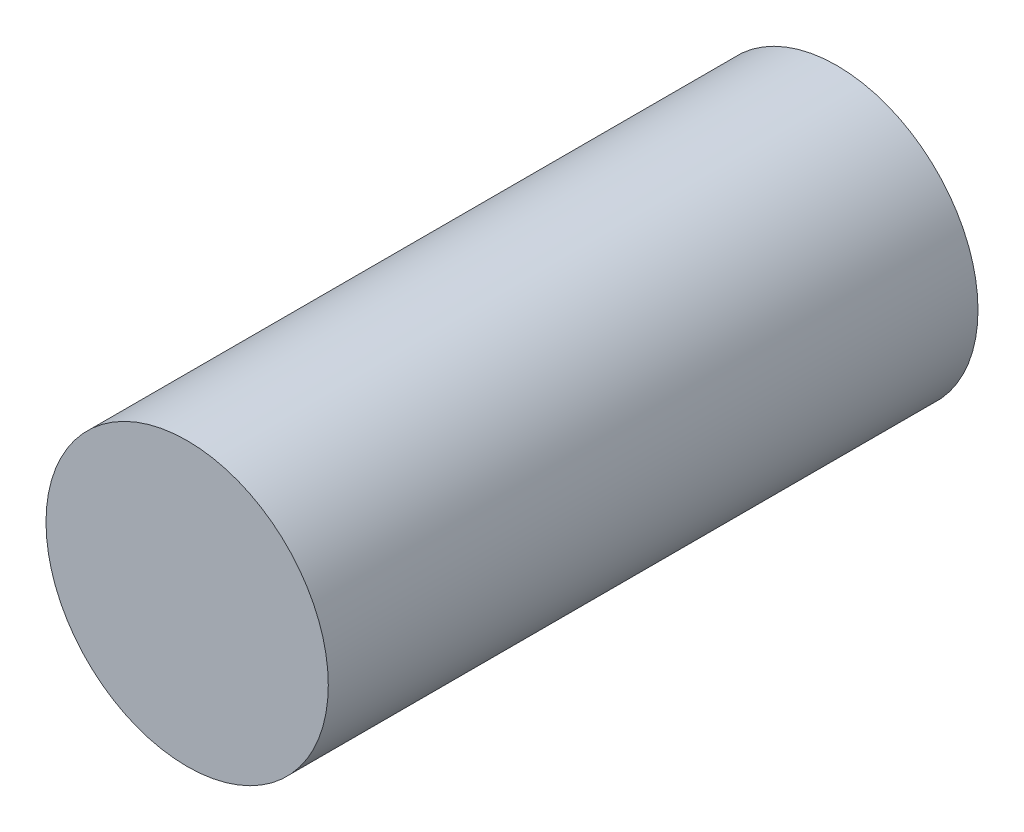
SolidWorks part; units mm, degrees
ref_plane "Front Plane" through (0, 0, 0) normal (1, 0, 0) x (0, 1, 0)
ref_plane "Top Plane" through (0, 0, 0) normal (0, 0, 1) x (0, 1, 0)
ref_plane "Right Plane" through (0, 0, 0) normal (0, 1, 0) x (-1, 0, 0)
sketch "Sketch3" plane through (0, 0, 0) normal (0, 0, 1) x (0, 1, 0)
  circle A0 centre (0, 0) radius 8.9074
extrude "Boss-Extrude1" add sketch "Sketch3" along normal blind 41
